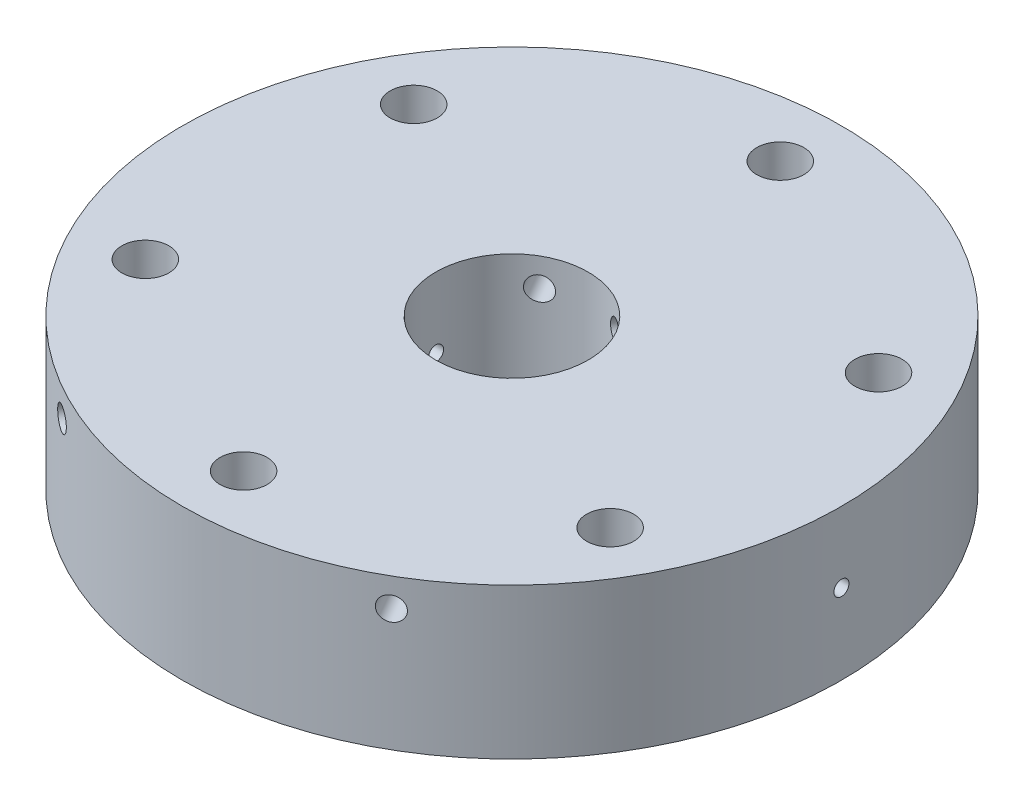
SolidWorks part; units mm, degrees
ref_plane "Front Plane" through (0, 0, 0) normal (0, 0, 1) x (1, 0, 0)
ref_plane "Top Plane" through (0, 0, 0) normal (0, 1, 0) x (1, 0, 0)
ref_plane "Right Plane" through (0, 0, 0) normal (1, 0, 0) x (0, 0, -1)
sketch "Sketch1" plane through (0, 0, 0) normal (0, 1, 0) x (1, 0, 0)
  circle A0 centre (0, 0) radius 88.9
  dimension "D1" = 177.8
extrude "Boss-Extrude1" add sketch "Sketch1" along normal blind 40.64 contours A0
sketch "Sketch2" plane through (0, 40.64, 0) normal (0, 1, 0) x (1, 0, 0)
  circle A0 centre (0, 0) radius 20.574
  dimension "D1" = 41.148
extrude "Cut-Extrude1" cut sketch "Sketch2" against normal through all
sketch "Sketch3" plane through (0, 0, 0) normal (1, 0, 0) x (0, 0, -1)
  line L0 (0, 0) -> (0, 21.59) construction
  line L2 (-88.9, 0) -> (88.9, 0) construction
  circle A0 centre (0, 21.59) radius 2.032
  point P3 (0, 25.5541)
  dimension "D1" = 4.064
  dimension "D2" = 21.59
extrude "Cut-Extrude4" cut sketch "Sketch3" against normal through all both and the other way through all
sketch "Sketch5" plane through (0, 0, 0) normal (1, 0, 0) x (0, 0, -1)
  line L0 (0, 0) -> (0, 50000) construction
  line L1 (0, 0) -> (50000, 0) construction
  line L2 (-20.574, 0) -> (20.574, 0) construction
  point P7 (0, 0)
ref_plane "Plane2" through (0, 0, 0) normal (0.5, 0, -0.866) x (0, 1, 0)
sketch "Sketch6" plane through (0, 0, 0) normal (0.5, 0, -0.866) x (0, 1, 0)
  line L2 (-200000, 0) -> (250000, 0) construction
  line L3 (40.64, -88.9) -> (40.64, 88.9) construction
  circle A1 centre (33.02, 0) radius 3.175
  dimension "D1" = 6.35
  dimension "D2" = 7.62
extrude "Cut-Extrude5" cut sketch "Sketch6" against normal through all both and the other way through all
mirror "Mirror1" about plane through (0, 0, 0) normal (0, 0, 1) of "Cut-Extrude5"
sketch "Sketch7" plane through (0, 0, 0) normal (0, -1, 0) x (1, 0, 0)
  line L0 (0, 0) -> (0, 50000) construction
  circle A0 centre (0, 0) radius 72.39 construction
  dimension "D1" = 144.78
hole_wizard "1/2 (0.5) Diameter Hole1" positions "3DSketch1" profile "Sketch8" hole size "1/2" standard "ANSI Inch" end condition through all
sketch3d "3DSketch1"
  line L0 (0, 0, 0) -> (0, 0, 50000) construction
  circle A0 centre (0, 0, 0) radius 72.39 construction
  point P0 (0, 0, 72.39)
  point P6 (0, -72.39, 0)
sketch "Sketch8" plane through (0, 0, 72.39) normal (1, 0, 0) x (0, 0, -1)
  line L0 (0, 0) -> (0, 40.64)
  line L1 (0, 40.64) -> (6.35, 40.64)
  line L2 (6.35, 40.64) -> (6.35, 0.635)
  line L3 (6.35, 0.635) -> (6.985, 0)
  line L5 (6.985, 0) -> (0, 0)
  line L6 (-6.35, 0.635) -> (-6.985, 0) construction
  line L11 (0, -6.35) -> (0, 107.95) construction
  dimension "Thru Hole Dia." = 12.7
  dimension "Thru Hole Depth" = 40.64
  dimension "Near C'Sink Dia." = 13.97
  dimension "Near C'Sink Angle" = 90
pattern_circular "CirPattern1" count 6 over 360 about axis through (0, 0, 0) along (0, 1, 0) of "1/2 (0.5) Diameter Hole1"
sketch "Sketch9" plane through (0, 0, 0) normal (0, 0, 1) x (1, 0, 0)
  line L0 (-72.39, 0) -> (72.39, 0) construction
  line L1 (45.72, 0) -> (55.88, 0)
  line L2 (45.72, 0) -> (45.72, 5.08)
  line L3 (45.72, 5.08) -> (55.88, 5.08)
  line L4 (55.88, 0) -> (55.88, 5.08)
  point P6 (50.8, 0)
  dimension "D1" = 10.16
  dimension "D2" = 5.08
  dimension "D3" = 50.8
revolve "Cut-Revolve1" cut sketch "Sketch9" angle 360 about axis through (0, 40.64, 0) along (0, -1, 0)
equation "\"D2@Sketch9\"=\"D1@Sketch9\"/2"
